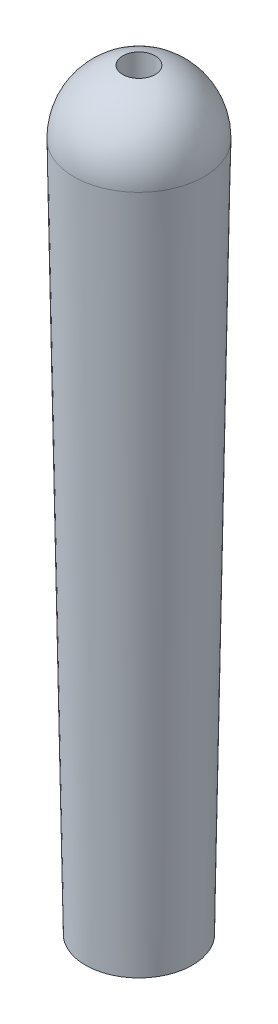
SolidWorks part; units mm, degrees
ref_plane "Front Plane" through (0, 0, 0) normal (0, 0, 1) x (1, 0, 0)
ref_plane "Top Plane" through (0, 0, 0) normal (0, 1, 0) x (1, 0, 0)
ref_plane "Right Plane" through (0, 0, 0) normal (1, 0, 0) x (0, 0, -1)
sketch "Sketch1" plane through (0, 0, 0) normal (0, 0, 1) x (1, 0, 0)
  line L0 (66.7177, 49.0463) -> (66.7177, 251.1297)
  line L1 (66.7177, 251.1297) -> (47.6132, 251.1297)
  line L2 (47.6132, 251.1297) -> (51.0096, 49.0463)
  line L3 (51.0096, 49.0463) -> (66.7177, 49.0463)
revolve "Revolve1" add sketch "Sketch1" angle 360 about L0
sketch "Sketch4" plane through (0, 0, 0) normal (0, 0, 1) x (1, 0, 0)
  line L0 (47.6132, 251.1297) -> (51.0096, 49.0463) construction
  line L1 (66.7177, 251.1297) -> (66.7177, 270.558)
  line L2 (85.8222, 251.1297) -> (47.6132, 251.1297) construction
  line L3 (47.6132, 251.1297) -> (66.7177, 251.1297)
  arc A0 (47.6132, 251.1297) -> (66.7177, 270.558) centre (66.7177, 251.4508) cw
revolve "Revolve3" add sketch "Sketch4" angle 360 about L1
sketch "Sketch5" plane through (0, 49.0463, 0) normal (0, -1, 0) x (1, 0, 0)
  circle A0 centre (66.7177, 0) radius 4.7625
  dimension "D1" = 9.525
extrude "Cut-Extrude2" cut sketch "Sketch5" against normal through all
